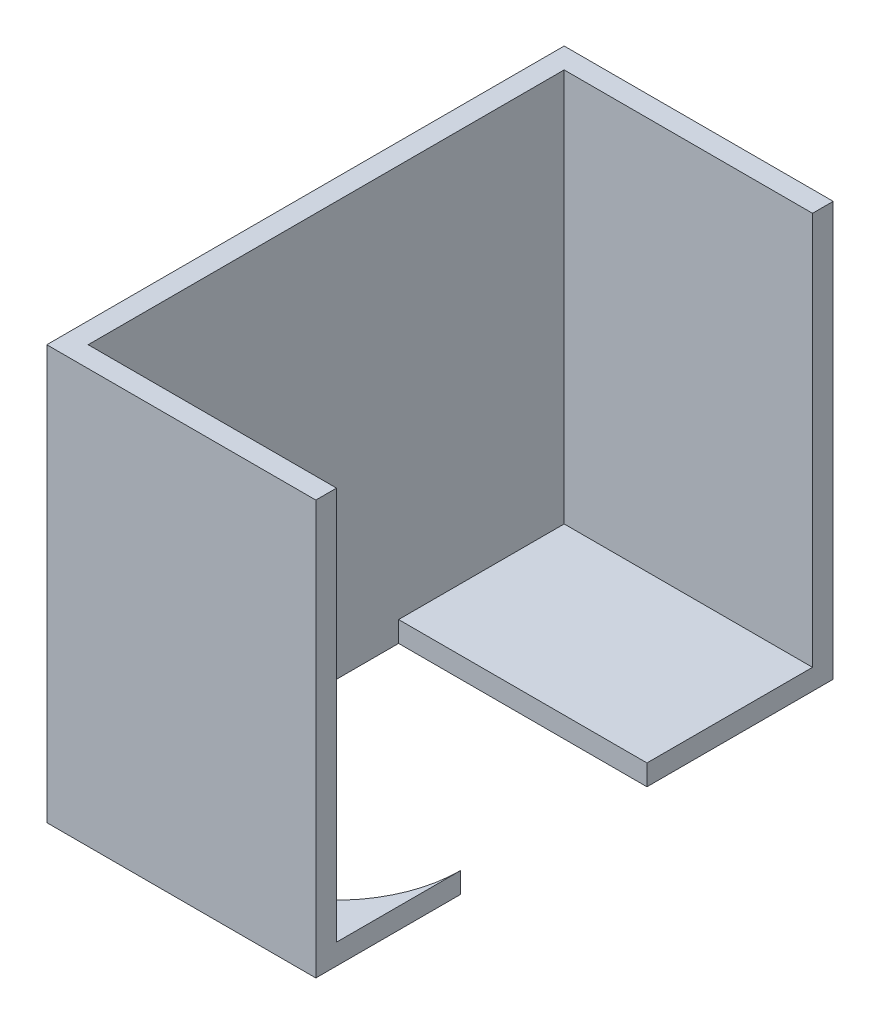
SolidWorks part; units mm, degrees
ref_plane "정면" through (0, 0, 0) normal (0, 0, 1) x (1, 0, 0)
ref_plane "윗면" through (0, 0, 0) normal (0, 1, 0) x (1, 0, 0)
ref_plane "우측면" through (0, 0, 0) normal (1, 0, 0) x (0, 0, -1)
sketch "스케치15" plane through (0, 0, 0) normal (0, 1, 0) x (1, 0, 0)
  line L1 (-6, -12.5) -> (7, -12.5)
  line L2 (-6, -12.5) -> (-6, 12.5)
  line L3 (-6, 12.5) -> (7, 12.5)
  line L4 (7, -12.5) -> (7, 12.5)
  dimension "D1" = 13
  dimension "D2" = 25
extrude "보스-돌출4" add sketch "스케치15" along normal blind 20
sketch "스케치16" plane through (0, 0, 0) normal (0, 1, 0) x (1, 0, 0)
  line L0 (7, -12.5) -> (7, 12.5) construction
  line L1 (-5, 11.5) -> (7, 11.5)
  line L2 (-5, 11.5) -> (-5, -11.5)
  line L3 (-5, -11.5) -> (7, -11.5)
  line L4 (7, 11.5) -> (7, -11.5)
  line L5 (-6, -12.5) -> (7, -12.5) construction
  dimension "D1" = 12
  dimension "D2" = 23
  dimension "D3" = 1
extrude "컷-돌출47" cut sketch "스케치16" along normal through all from offset 1
sketch "스케치17" plane through (0, 0, 0) normal (0, 1, 0) x (1, 0, 0)
  line L0 (-5, -11.5) -> (7, -11.5) construction
  line L1 (-5, 11.5) -> (-5, -11.5) construction
  line L3 (-5, 3.5) -> (7, 3.5)
  line L4 (-5, 3.5) -> (-5, -5.5)
  line L6 (7, 3.5) -> (7, -5.5)
  arc A0 (-5, -5.5) -> (7, -5.5) centre (1, -5.5) ccw
  dimension "D1" = 12
  dimension "D2" = 12
  dimension "D3" = 9
extrude "컷-돌출48" cut sketch "스케치17" along normal through all
